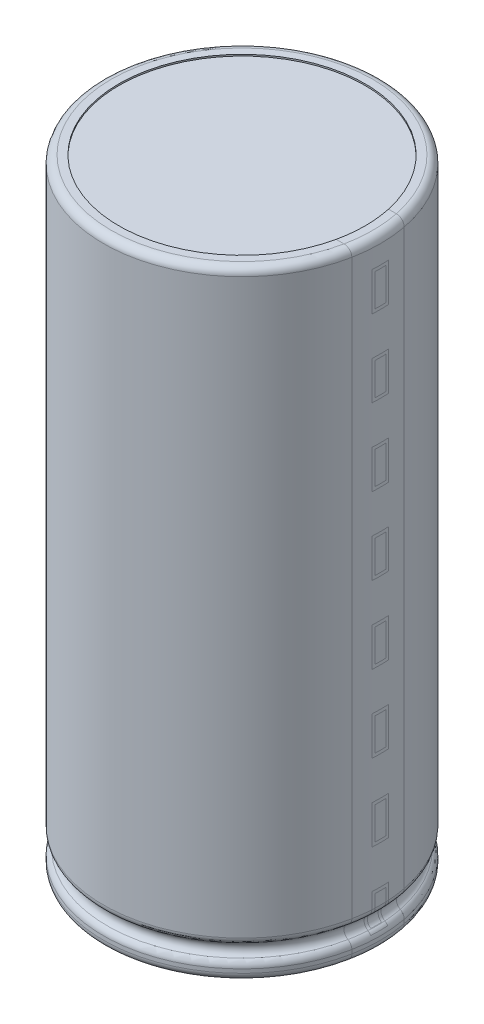
SolidWorks part; units mm, degrees
ref_plane "Front Plane" through (0, 0, 0) normal (0, 0, 1) x (1, 0, 0)
ref_plane "Top Plane" through (0, 0, 0) normal (0, 1, 0) x (1, 0, 0)
ref_plane "Right Plane" through (0, 0, 0) normal (1, 0, 0) x (0, 0, -1)
sketch "Sketch1" plane through (0, 0, 0) normal (0, 1, 0) x (1, 0, 0)
  line L0 (-3.75, 0) -> (3.75, 0) construction
  circle A0 centre (-3.75, 0) radius 0.4
  circle A1 centre (3.75, 0) radius 0.4
  dimension "D3" = 0.8
  dimension "D1" = 7.5
extrude "Boss-Extrude1" add sketch "Sketch1" against normal blind 3 and the other way blind 1
sketch "Sketch3" plane through (0, 0, 0) normal (0, 0, 1) x (1, 0, 0)
  line L1 (0, 0.1) -> (0, 40.2) construction
  line L2 (9, 0.5) -> (9, 0.75)
  line L3 (0, 0.1) -> (8, 0.1)
  line L4 (8, 40.2) -> (8.5, 40.2)
  line L5 (8, 0) -> (8.5, 0)
  line L6 (0, 40.1) -> (8, 40.1)
  line L7 (9, 2.4821) -> (9, 39.7)
  line L8 (8, 40.1) -> (8, 40.2)
  line L9 (9, 2.4821) -> (9, 40.2) construction
  line L10 (8, 0) -> (8, 0.1)
  line L11 (0, 40.1) -> (9, 40.1) construction
  line L12 (0, 40.2) -> (9, 40.2) construction
  line L13 (8, 2.4821) -> (8, 40.2) construction
  line L14 (0, 0.1) -> (0, 40.1)
  line L17 (0, 0.1) -> (5, 0.1) construction
  line L18 (0, 0) -> (5, 0) construction
  arc A0 (8.75, 2.049) -> (8.75, 1.183) centre (9, 1.616) ccw
  arc A1 (9, 0.75) -> (8.75, 1.183) centre (8.5, 0.75) ccw
  arc A2 (9, 2.4821) -> (8.75, 2.049) centre (8.5, 2.4821) cw
  arc A3 (9, 39.7) -> (8.5, 40.2) centre (8.5, 39.7) ccw
  arc A4 (8.5, 0) -> (9, 0.5) centre (8.5, 0.5) ccw
  point P1 (0, 0)
  point P2 (0, 20.2)
  point P13 (9, 2.116)
  point P29 (0, 0)
  point P32 (8.5, 1.616)
  dimension "D2" = 0.5
  dimension "D1" = 0.5
  dimension "D3" = 40
  dimension "D6" = 1
  dimension "D7" = 0.1
  dimension "D10" = 0.25
  dimension "D11" = 16
  dimension "D4" = 18
  dimension "D12" = 17
  dimension "D5" = 1
revolve "Revolve1" add sketch "Sketch3" angle 360 about L14
sketch "Sketch4" plane through (0, 0, 0) normal (1, 0, 0) x (0, 0, -1)
  line L0 (-8.5, 0) -> (8.5, 0) construction
  line L1 (-1.7, 0) -> (1.7, 0)
  line L2 (0, 0) -> (0, 40.2) construction
  line L3 (-1.7, 40.2) -> (1.7, 40.2)
  line L4 (1.7, 0) -> (1.7, 40.2)
  line L5 (8, 40.2) -> (-8, 40.2) construction
  line L6 (-1.7, 0) -> (-1.7, 40.2)
  line L7 (-0.35, 13.3) -> (-0.35, 11.2)
  line L8 (-0.35, 13.3) -> (0.35, 13.3)
  line L9 (0, 13.3) -> (0, 11.2) construction
  line L10 (-0.35, 11.2) -> (0.35, 11.2)
  line L11 (0.35, 13.3) -> (0.35, 11.2)
  line L12 (0.55, 13.5) -> (0.55, 11)
  line L13 (-0.55, 11) -> (0.55, 11)
  line L14 (-0.55, 13.5) -> (-0.55, 11)
  line L15 (-0.55, 13.5) -> (0.55, 13.5)
  line L16 (0, 0) -> (0, -3.7489) construction
  line L17 (-0.35, 8.3) -> (-0.35, 6.2)
  line L18 (-0.35, 8.3) -> (0.35, 8.3)
  line L19 (-0.35, 6.2) -> (0.35, 6.2)
  line L20 (0.35, 8.3) -> (0.35, 6.2)
  line L21 (0.55, 8.5) -> (0.55, 6)
  line L22 (-0.55, 6) -> (0.55, 6)
  line L23 (-0.55, 8.5) -> (-0.55, 6)
  line L24 (-0.55, 8.5) -> (0.55, 8.5)
  line L25 (0, 8.3) -> (0, 6.2) construction
  line L26 (-0.35, 3.3) -> (-0.35, 1.2)
  line L27 (-0.35, 3.3) -> (0.35, 3.3)
  line L28 (-0.35, 1.2) -> (0.35, 1.2)
  line L29 (0.35, 3.3) -> (0.35, 1.2)
  line L30 (0.55, 3.5) -> (0.55, 1)
  line L31 (-0.55, 1) -> (0.55, 1)
  line L32 (-0.55, 3.5) -> (-0.55, 1)
  line L33 (-0.55, 3.5) -> (0.55, 3.5)
  line L34 (0, 3.3) -> (0, 1.2) construction
  line L35 (-0.55, 18.5) -> (0.55, 18.5)
  line L36 (-0.55, 18.5) -> (-0.55, 16)
  line L37 (-0.35, 18.3) -> (0.35, 18.3)
  line L38 (0.35, 18.3) -> (0.35, 16.2)
  line L39 (0.55, 18.5) -> (0.55, 16)
  line L40 (-0.35, 18.3) -> (-0.35, 16.2)
  line L41 (-0.35, 16.2) -> (0.35, 16.2)
  line L42 (-0.55, 16) -> (0.55, 16)
  line L43 (-0.55, 23.5) -> (0.55, 23.5)
  line L44 (-0.55, 23.5) -> (-0.55, 21)
  line L45 (-0.35, 23.3) -> (0.35, 23.3)
  line L46 (0.35, 23.3) -> (0.35, 21.2)
  line L47 (0.55, 23.5) -> (0.55, 21)
  line L48 (-0.35, 23.3) -> (-0.35, 21.2)
  line L49 (-0.35, 21.2) -> (0.35, 21.2)
  line L50 (-0.55, 21) -> (0.55, 21)
  line L51 (-0.55, 11) -> (-0.55, 8.5) construction
  line L52 (-0.55, 13.5) -> (-0.55, 16) construction
  line L53 (-0.55, 28.5) -> (0.55, 28.5)
  line L54 (-0.55, 28.5) -> (-0.55, 26)
  line L55 (-0.35, 28.3) -> (0.35, 28.3)
  line L56 (0.35, 28.3) -> (0.35, 26.2)
  line L57 (0.55, 28.5) -> (0.55, 26)
  line L58 (-0.35, 28.3) -> (-0.35, 26.2)
  line L59 (-0.35, 26.2) -> (0.35, 26.2)
  line L60 (-0.55, 26) -> (0.55, 26)
  line L61 (-0.55, 33.5) -> (0.55, 33.5)
  line L62 (-0.55, 33.5) -> (-0.55, 31)
  line L63 (-0.35, 33.3) -> (0.35, 33.3)
  line L64 (0.35, 33.3) -> (0.35, 31.2)
  line L65 (0.55, 33.5) -> (0.55, 31)
  line L66 (-0.35, 33.3) -> (-0.35, 31.2)
  line L67 (-0.35, 31.2) -> (0.35, 31.2)
  line L68 (-0.55, 31) -> (0.55, 31)
  line L69 (-0.55, 38.5) -> (0.55, 38.5)
  line L70 (-0.55, 38.5) -> (-0.55, 36)
  line L71 (-0.35, 38.3) -> (0.35, 38.3)
  line L72 (0.35, 38.3) -> (0.35, 36.2)
  line L73 (0.55, 38.5) -> (0.55, 36)
  line L74 (-0.35, 38.3) -> (-0.35, 36.2)
  line L75 (-0.35, 36.2) -> (0.35, 36.2)
  line L76 (-0.55, 36) -> (0.55, 36)
  point P64 (0, 18.3)
  dimension "D5" = 3.4
  dimension "D6" = 0.2
  dimension "D7" = 1.1
  dimension "D8" = 2.1
  dimension "D1" = 0.7
  dimension "D9" = 1
  dimension "D10" = 2.5
  dimension "D2" = 3
  dimension "D3" = 6
split line "Split Line1"
